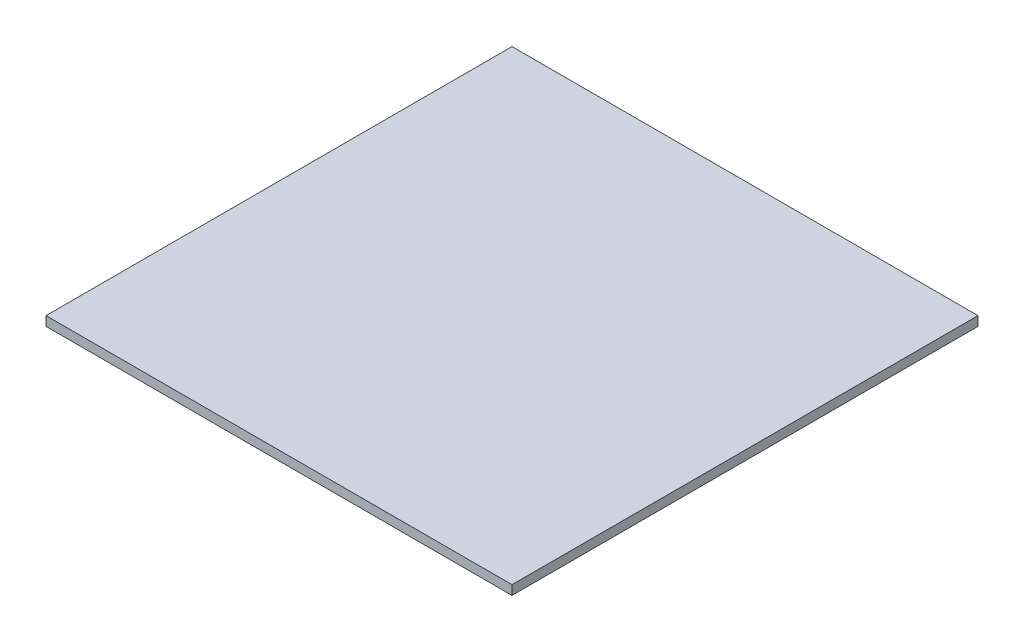
SolidWorks part; units mm, degrees
ref_plane "Alzado" through (0, 0, 0) normal (0, 0, 1) x (1, 0, 0)
ref_plane "Planta" through (0, 0, 0) normal (0, 1, 0) x (1, 0, 0)
ref_plane "Vista lateral" through (0, 0, 0) normal (1, 0, 0) x (0, 0, -1)
sketch "Croquis1" plane through (0, 0, 0) normal (0, 1, 0) x (1, 0, 0)
  line L1 (0, 0) -> (100, 0)
  line L2 (0, 0) -> (0, 100)
  line L3 (0, 100) -> (100, 100)
  line L4 (100, 0) -> (100, 100)
  dimension "D1" = 100
extrude "Saliente-Extruir1" add sketch "Croquis1" along normal blind 2
